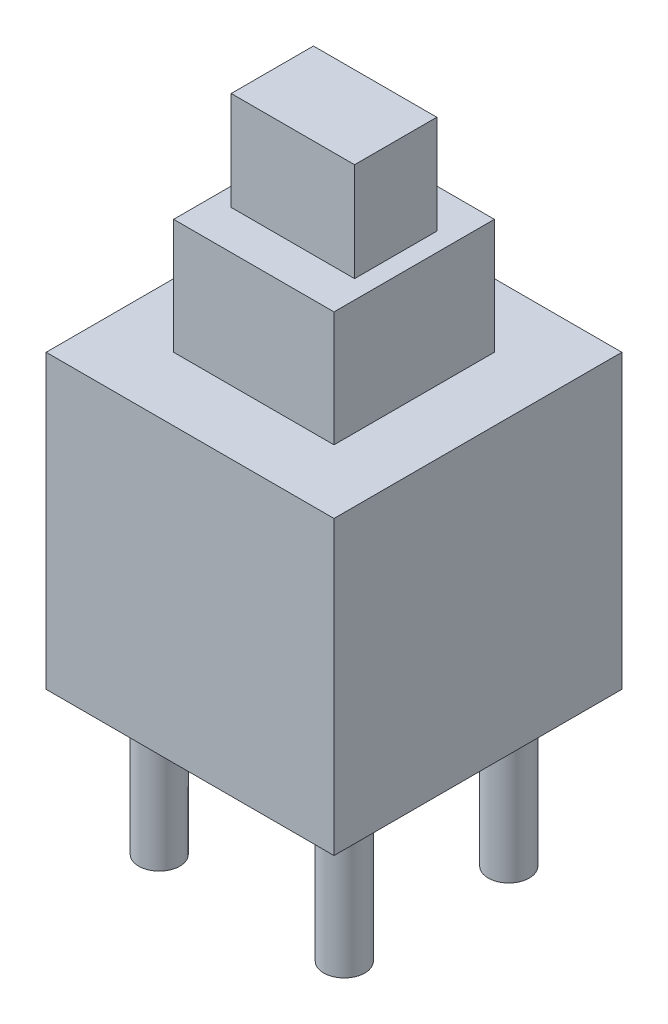
SolidWorks part; units mm, degrees
ref_plane "前视基准面" through (0, 0, 0) normal (0, 0, 1) x (1, 0, 0)
ref_plane "上视基准面" through (0, 0, 0) normal (0, 1, 0) x (1, 0, 0)
ref_plane "右视基准面" through (0, 0, 0) normal (1, 0, 0) x (0, 0, -1)
other "Configuration Table"
sketch "草图1" plane through (0, 0, 0) normal (0, 1, 0) x (1, 0, 0)
  line L1 (0, 0) -> (7, 0)
  line L2 (0, 0) -> (0, 7)
  line L3 (0, 7) -> (7, 7)
  line L4 (7, 0) -> (7, 7)
  dimension "D1" = 7
  dimension "D2" = 7
extrude "凸台-拉伸1" add sketch "草图1" along normal blind 7.1
sketch "草图2" plane through (0, 7.1, 0) normal (0, 1, 0) x (1, 0, 0)
  line L0 (3.5, 7) -> (3.5, 0) construction
  line L1 (7, 7) -> (0, 7) construction
  line L2 (0, 0) -> (7, 0) construction
  line L3 (1.55, 5.45) -> (5.45, 1.55) construction
  line L4 (1.55, 5.45) -> (5.45, 5.45)
  line L5 (1.55, 5.45) -> (1.55, 1.55)
  line L6 (1.55, 1.55) -> (5.45, 1.55)
  line L7 (5.45, 5.45) -> (5.45, 1.55)
  point P10 (3.5, 3.5)
  dimension "D1" = 3.9
extrude "凸台-拉伸2" add sketch "草图2" along normal blind 2.8
sketch "草图3" plane through (0, 0, 0) normal (0, -1, 0) x (1, 0, 0)
  line L0 (3.5, 0) -> (3.5, -7) construction
  line L1 (0, 0) -> (7, 0) construction
  line L2 (7, -7) -> (0, -7) construction
  line L3 (0, -3.5) -> (7, -3.5) construction
  line L4 (0, -7) -> (0, 0) construction
  line L5 (7, 0) -> (7, -7) construction
  circle A0 centre (1.25, -1.5) radius 0.5
  circle A1 centre (5.75, -1.5) radius 0.5
  circle A2 centre (5.75, -5.5) radius 0.5
  circle A3 centre (1.25, -5.5) radius 0.5
  dimension "D1" = 1
  dimension "D2" = 4.5
  dimension "D3" = 4
extrude "凸台-拉伸3" add sketch "草图3" along normal blind 3.6
sketch "草图4" plane through (0, 9.9, 0) normal (0, 1, 0) x (1, 0, 0)
  line L0 (3.5, 5.45) -> (3.5, 4.5) construction
  line L1 (2, 4.5) -> (5, 4.5)
  line L2 (2, 4.5) -> (2, 2.5)
  line L3 (2, 2.5) -> (5, 2.5)
  line L4 (5, 4.5) -> (5, 2.5)
  line L5 (5.45, 5.45) -> (1.55, 5.45) construction
  line L6 (1.55, 3.5) -> (2, 3.5) construction
  line L7 (1.55, 5.45) -> (1.55, 1.55) construction
  dimension "D1" = 3
  dimension "D2" = 2
extrude "凸台-拉伸4" add sketch "草图4" along normal offset from surface (2.4 mm away) 12.3 up to face at (1.25, 0, -6)
